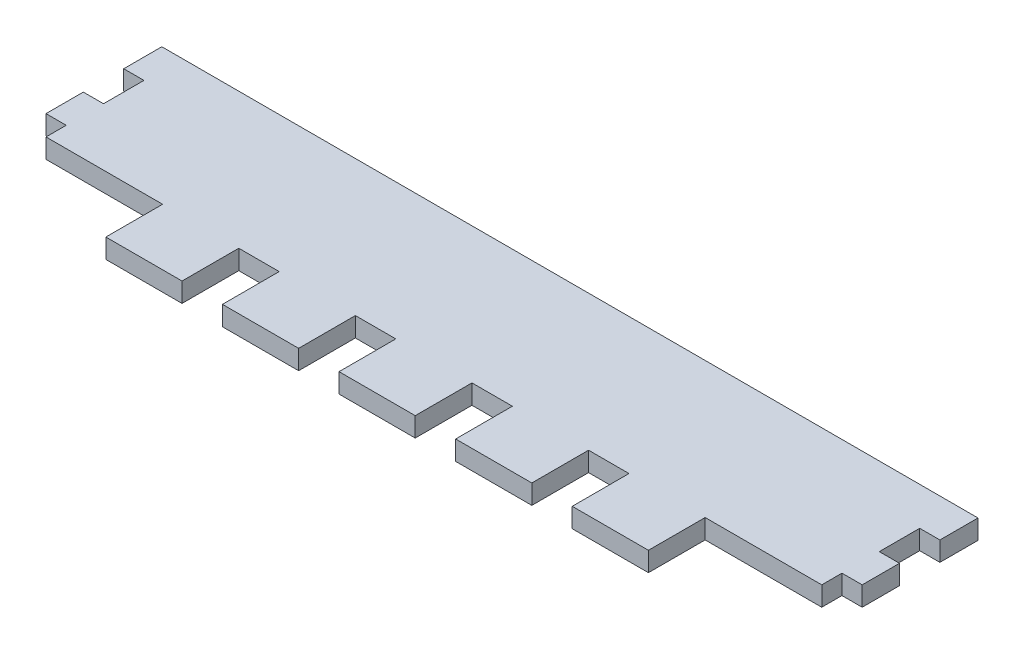
SolidWorks part; units mm, degrees
ref_plane "Front Plane" through (0, 0, 0) normal (0, 0, 1) x (1, 0, 0)
ref_plane "Top Plane" through (0, 0, 0) normal (0, 1, 0) x (1, 0, 0)
ref_plane "Right Plane" through (0, 0, 0) normal (1, 0, 0) x (0, 0, -1)
sketch "Sketch1" plane through (0, 0, 0) normal (0, 1, 0) x (1, 0, 0)
  line L2 (-133.35, -28.575) -> (-133.35, 28.575)
  line L3 (-133.35, 28.575) -> (133.35, 28.575)
  line L4 (133.35, -28.575) -> (133.35, 28.575)
  line L5 (-133.35, -28.575) -> (133.35, 28.575) construction
  line L6 (-133.35, 28.575) -> (133.35, -28.575) construction
  line L11 (-133.35, -28.575) -> (133.35, -28.575)
  point P0 (0, 0)
  dimension "D1" = 57.15
  dimension "D2" = 266.7
extrude "Boss-Extrude1" add sketch "Sketch1" along normal blind 6.35
sketch "Sketch3" plane through (0, 0, 0) normal (0, 1, 0) x (1, 0, 0)
  line L0 (-133.35, -28.575) -> (133.35, -28.575) construction
  line L1 (-88.646, -28.575) -> (-88.646, -47.117)
  line L2 (-88.646, -47.117) -> (-63.754, -47.117)
  line L3 (-63.754, -47.117) -> (-63.754, -28.575)
  line L4 (-63.754, -28.575) -> (-88.646, -28.575)
  line L5 (-50.546, -28.575) -> (-50.546, -47.117)
  line L6 (-50.546, -47.117) -> (-25.654, -47.117)
  line L7 (-25.654, -47.117) -> (-25.654, -28.575)
  line L8 (-25.654, -28.575) -> (-50.546, -28.575)
  line L9 (-12.446, -28.575) -> (-12.446, -47.117)
  line L10 (-12.446, -47.117) -> (12.446, -47.117)
  line L11 (12.446, -47.117) -> (12.446, -28.575)
  line L12 (12.446, -28.575) -> (-12.446, -28.575)
  line L13 (25.654, -28.575) -> (25.654, -47.117)
  line L14 (25.654, -47.117) -> (50.546, -47.117)
  line L15 (50.546, -47.117) -> (50.546, -28.575)
  line L16 (50.546, -28.575) -> (25.654, -28.575)
  line L17 (63.754, -28.575) -> (63.754, -47.117)
  line L18 (63.754, -47.117) -> (88.646, -47.117)
  line L19 (88.646, -47.117) -> (88.646, -28.575)
  line L20 (88.646, -28.575) -> (63.754, -28.575)
  point P0 (-76.2, -28.575)
  point P6 (-38.1, -28.575)
  point P14 (0, -28.575)
  point P19 (38.1, -28.575)
  point P24 (76.2, -28.575)
  dimension "D1" = 24.892
  dimension "D2" = 18.542
  dimension "D3" = 57.15
  dimension "D4" = 5
extrude "Boss-Extrude2" add sketch "Sketch3" along normal blind 6.35
sketch "Sketch4" plane through (0, 0, 0) normal (0, 1, 0) x (1, 0, 0)
  line L0 (133.35, 28.575) -> (-133.35, 28.575) construction
  line L6 (-139.954, 28.829) -> (-126.746, 28.829)
  line L7 (-139.954, 28.829) -> (-139.954, 15.621)
  line L8 (0, 0) -> (0, 63.6475) construction
  line L13 (133.35, -28.575) -> (133.35, 28.575) construction
  line L14 (126.746, 28.829) -> (139.954, 28.829)
  line L30 (126.746, 28.829) -> (126.746, 15.621)
  line L31 (126.746, 15.621) -> (139.954, 15.621)
  line L32 (139.954, 28.829) -> (139.954, 15.621)
  line L33 (126.746, 28.829) -> (139.954, 15.621) construction
  line L34 (126.746, 15.621) -> (139.954, 28.829) construction
  line L36 (-139.954, 15.621) -> (-126.746, 15.621)
  line L37 (-126.746, 28.829) -> (-126.746, 15.621)
  line L38 (-139.954, 28.829) -> (-126.746, 15.621) construction
  line L39 (-139.954, 15.621) -> (-126.746, 28.829) construction
  line L40 (-139.954, 3.429) -> (-126.746, 3.429)
  line L41 (-139.954, 3.429) -> (-139.954, -9.779)
  line L42 (-139.954, -9.779) -> (-126.746, -9.779)
  line L43 (-126.746, 3.429) -> (-126.746, -9.779)
  line L44 (-139.954, 3.429) -> (-126.746, -9.779) construction
  line L45 (-139.954, -9.779) -> (-126.746, 3.429) construction
  line L46 (-139.954, -21.971) -> (-126.746, -21.971)
  line L47 (-139.954, -21.971) -> (-139.954, -35.179)
  line L48 (-139.954, -35.179) -> (-126.746, -35.179)
  line L49 (-126.746, -21.971) -> (-126.746, -35.179)
  line L50 (-139.954, -21.971) -> (-126.746, -35.179) construction
  line L51 (-139.954, -35.179) -> (-126.746, -21.971) construction
  line L52 (126.746, 3.429) -> (139.954, 3.429)
  line L53 (126.746, 3.429) -> (126.746, -9.779)
  line L54 (126.746, -9.779) -> (139.954, -9.779)
  line L55 (139.954, 3.429) -> (139.954, -9.779)
  line L56 (126.746, 3.429) -> (139.954, -9.779) construction
  line L57 (126.746, -9.779) -> (139.954, 3.429) construction
  line L58 (126.746, -21.971) -> (139.954, -21.971)
  line L59 (126.746, -21.971) -> (126.746, -35.179)
  line L60 (126.746, -35.179) -> (139.954, -35.179)
  line L61 (139.954, -21.971) -> (139.954, -35.179)
  line L62 (126.746, -21.971) -> (139.954, -35.179) construction
  line L63 (126.746, -35.179) -> (139.954, -21.971) construction
  point P4 (-133.35, 22.225)
  point P10 (-133.35, -3.175)
  point P13 (133.35, 22.225)
  point P23 (-133.35, -28.575)
  point P29 (133.35, -3.175)
  point P34 (133.35, -28.575)
  dimension "D1" = 3
  dimension "D4" = 13.208
  dimension "D6" = 13.208
  dimension "D7" = 6.35
extrude "Cut-Extrude2" cut sketch "Sketch4" along normal through all
sketch "Sketch5" plane through (0, 6.35, 0) normal (0, 1, 0) x (1, 0, 0)
  line L0 (126.746, 28.575) -> (-126.746, 28.575) construction
  line L1 (-139.7688, 28.575) -> (155.6953, 28.575)
  line L2 (-139.7688, 28.575) -> (-139.7688, 15.875)
  line L3 (-139.7688, 15.875) -> (155.6953, 15.875)
  line L4 (155.6953, 28.575) -> (155.6953, 15.875)
  dimension "D1" = 12.7
extrude "Cut-Extrude3" cut sketch "Sketch5" against normal through all
sketch "Sketch6" plane through (0, 6.35, 0) normal (0, 1, 0) x (1, 0, 0)
  line L0 (133.35, 3.429) -> (133.35, 15.621) construction
  line L1 (-133.35, 3.429) -> (133.35, 3.429)
  line L2 (-133.35, 3.429) -> (-133.35, 15.875)
  line L3 (-133.35, 15.875) -> (133.35, 15.875)
  line L4 (133.35, 3.429) -> (133.35, 15.875)
  line L5 (-126.746, 15.875) -> (126.746, 15.875) construction
extrude "Boss-Extrude3" add sketch "Sketch6" against normal blind 6.35
